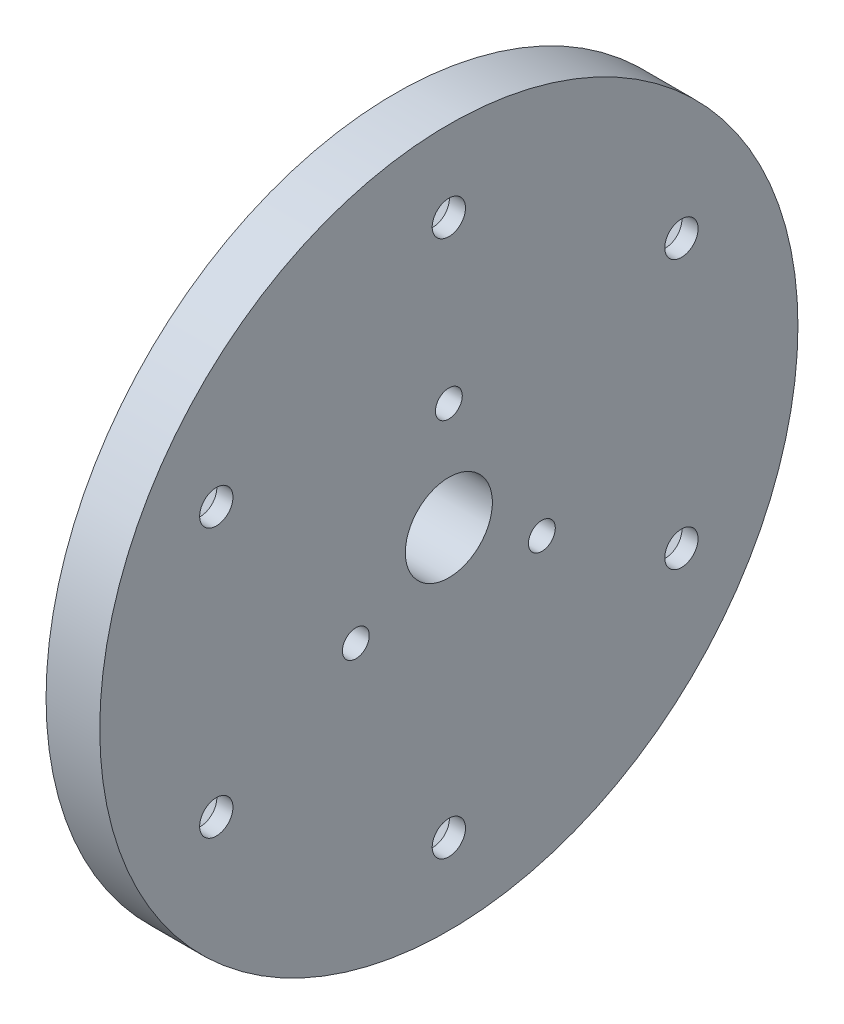
SolidWorks part; units mm, degrees
ref_plane "Ebene vorne" through (0, 0, 0) normal (0, 0, 1) x (1, 0, 0)
ref_plane "Ebene oben" through (0, 0, 0) normal (0, 1, 0) x (1, 0, 0)
ref_plane "Ebene rechts" through (0, 0, 0) normal (1, 0, 0) x (0, 0, -1)
sketch "Skizze1" plane through (0, 0, 0) normal (0, 0, 1) x (1, 0, 0)
  line L0 (0, 0) -> (-12136.2511, 0) construction
  line L1 (0, 0) -> (0, 16.5)
  line L2 (0, 16.5) -> (3, 16.5)
  line L3 (3, 16.5) -> (3, 32.5)
  line L4 (3, 32.5) -> (8, 32.5)
  line L5 (8, 32.5) -> (8, 0)
  line L6 (8, 0) -> (0, 0)
  dimension "D1" = 3
  dimension "D2" = 33
  dimension "D3" = 65
  dimension "D4" = 5
revolve "Rotation1" add sketch "Skizze1" angle 360 about L0
hole_wizard "Ø8.1 (8.1) Durchmesser Bohrung1" positions "Skizze2" profile "Skizze3" hole size "Ø8.1" standard "ISO" end condition through all
sketch "Skizze2" plane through (0, 0, 0) normal (-1, 0, 0) x (0, 0, 1)
  point P2 (0, 0)
sketch "Skizze3" plane through (0, 0, 0) normal (0, 1, 0) x (0, 0, 1)
  line L0 (0, 0) -> (0, 8)
  line L1 (0, 8) -> (4.05, 8)
  line L2 (4.05, 8) -> (4.05, 0)
  line L5 (4.05, 0) -> (0, 0)
  line L11 (0, -6.35) -> (0, 107.95) construction
  dimension "Bohrerdurchmesser" = 8.1
  dimension "Bohrungstiefe" = 8
sketch "Skizze4" plane through (8, 0, 0) normal (1, 0, 0) x (0, 0, -1)
  line L0 (0, 0) -> (0, 50000) construction
  circle A0 centre (0, 0) radius 10 construction
  circle A1 centre (0, 10) radius 1.25
  circle A2 centre (8.6603, -5) radius 1.25
  circle A3 centre (-8.6603, -5) radius 1.25
  point P15 (0, 0)
  dimension "D1" = 20
  dimension "D2" = 2.5
  dimension "D3" = 3
extrude "Schnitt-Linear austragen1" cut sketch "Skizze4" against normal through all
sketch "Skizze5" plane through (8, 0, 0) normal (1, 0, 0) x (0, 0, -1)
  line L0 (0, 0) -> (0, -50000) construction
  circle A0 centre (0, 0) radius 25 construction
  circle A1 centre (0, 25) radius 1.55
  circle A2 centre (21.6506, 12.5) radius 1.55
  circle A3 centre (21.6506, -12.5) radius 1.55
  circle A4 centre (0, -25) radius 1.55
  circle A5 centre (-21.6506, -12.5) radius 1.55
  circle A6 centre (-21.6506, 12.5) radius 1.55
  point P20 (0, 0)
  dimension "D1" = 3.1
  dimension "D2" = 50
  dimension "D3" = 6
extrude "Schnitt-Linear austragen2" cut sketch "Skizze5" against normal through all
chamfer "Fase2" distance 3.5 angle 45 6 edges at (3, -12.5, -20.1006) (3, -25, 1.55) (3, -12.5, 23.2006) (3, 12.5, 23.2006) (3, 25, 1.55) (3, 12.5, -20.1006)
